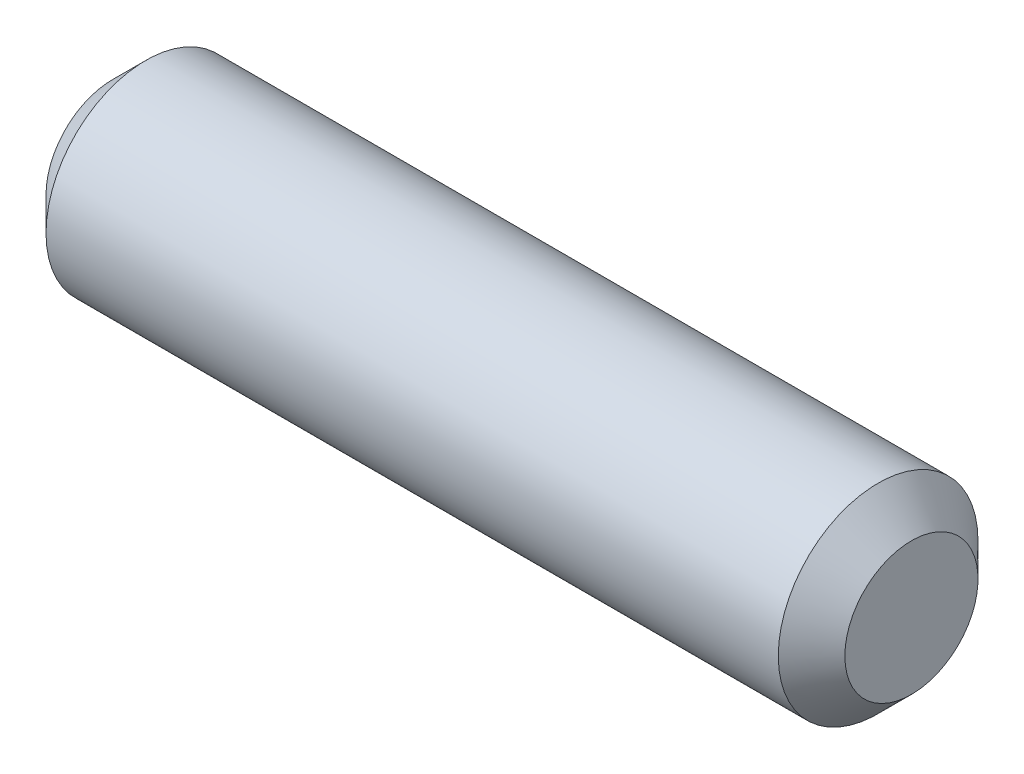
SolidWorks part; units mm, degrees
material "AISI 304"
ref_plane "Front Plane" through (0, 0, 0) normal (0, 0, 1) x (1, 0, 0)
ref_plane "Top Plane" through (0, 0, 0) normal (0, 1, 0) x (1, 0, 0)
ref_plane "Right Plane" through (0, 0, 0) normal (1, 0, 0) x (0, 0, -1)
sketch "Sketch1" plane through (0, 0, 0) normal (0, 0, 1) x (1, 0, 0)
  line L0 (-6, 0) -> (6, 0)
  line L1 (-6, -1.5) -> (6, -1.5)
  line L2 (-6, -1.5) -> (-6, 1.5)
  line L3 (-6, 1.5) -> (6, 1.5)
  line L4 (6, -1.5) -> (6, 1.5)
  line L5 (-6, -1.5) -> (6, 1.5) construction
  line L6 (-6, 1.5) -> (6, -1.5) construction
  point P0 (0, 0)
  dimension "D1" = 12
  dimension "D2" = 3
revolve "Revolve1" add sketch "Sketch1" angle 360 about L0
chamfer "Chamfer1" distance 0.5 angle 45 2 edges at (-6, 0, 1.5) (6, 0, 1.5)
